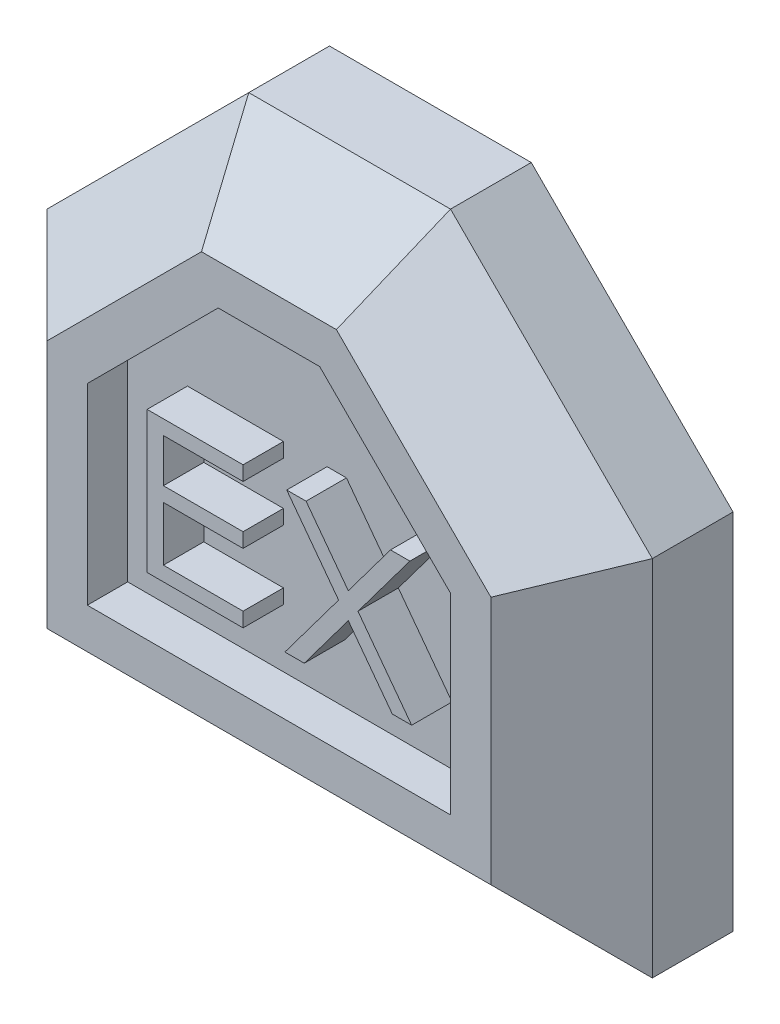
SolidWorks part; units mm, degrees
ref_plane "前视基准面" through (0, 0, 0) normal (0, 0, 1) x (1, 0, 0)
ref_plane "上视基准面" through (0, 0, 0) normal (0, 1, 0) x (1, 0, 0)
ref_plane "右视基准面" through (0, 0, 0) normal (1, 0, 0) x (0, 0, -1)
sketch "草图1" plane through (0, 0, 0) normal (0, 0, 1) x (1, 0, 0)
  line L0 (-7.5, 2) -> (-2.5, 7)
  line L1 (-7.5, -7) -> (7.5, -7)
  line L2 (-7.5, -7) -> (-7.5, 2)
  line L3 (-2.5, 7) -> (2.5, 7)
  line L4 (7.5, -7) -> (7.5, 2)
  line L5 (-7.5, -7) -> (7.5, 7) construction
  line L6 (-7.5, 7) -> (7.5, -7) construction
  line L7 (2.5, 7) -> (7.5, 2)
  point P0 (0, 0)
  dimension "D1" = 14
  dimension "D2" = 15
extrude "凸台-拉伸1" add sketch "草图1" along normal blind 4
chamfer "倒角1" distance 2 angle 45 6 edges at (-5, 4.5, 4) (0, 7, 4) (5, 4.5, 4) (7.5, -2.5, 4) (0, -7, 4) (-7.5, -2.5, 4)
sketch "草图2" plane through (0, 0, 4) normal (0, 0, 1) x (1, 0, 0)
  line L12 (5.8137, 15) -> (-5.8137, 15)
  line L13 (-5.8137, 15) -> (-15.5, 5.3137)
  line L14 (-15.5, 5.3137) -> (-15.5, -15)
  line L15 (-15.5, -15) -> (15.5, -15)
  line L16 (15.5, -15) -> (15.5, 5.3137)
  line L17 (15.5, 5.3137) -> (5.8137, 15)
  line L18 (5.8137, 15) -> (-5.8137, 15)
  line L19 (-5.8137, 15) -> (-15.5, 5.3137)
  line L20 (-15.5, 5.3137) -> (-15.5, -15)
  line L21 (-15.5, -15) -> (15.5, -15)
  line L22 (15.5, -15) -> (15.5, 5.3137)
  line L23 (15.5, 5.3137) -> (5.8137, 15)
  line L30 (-4.5, -4) -> (4.5, -4)
  line L31 (4.5, -4) -> (4.5, 0.7574)
  line L32 (4.5, 0.7574) -> (1.2574, 4)
  line L33 (1.2574, 4) -> (-1.2574, 4)
  line L34 (-1.2574, 4) -> (-4.5, 0.7574)
  line L35 (-4.5, 0.7574) -> (-4.5, -4)
  line L36 (-4.5, -4) -> (4.5, -4)
  line L37 (4.5, -4) -> (4.5, 0.7574)
  line L38 (4.5, 0.7574) -> (1.2574, 4)
  line L39 (1.2574, 4) -> (-1.2574, 4)
  line L40 (-1.2574, 4) -> (-4.5, 0.7574)
  line L41 (-4.5, 0.7574) -> (-4.5, -4)
  dimension "D1" = 10
  dimension "D2" = 1
extrude "切除-拉伸1" cut sketch "草图2" against normal blind 1 contours L40 L41 L36 L37 L38 L39
sketch "草图3" plane through (0, 0, 3) normal (0, 0, 1) x (1, 0, 0)
  text T0 "EX" font "Century Gothic" height 3.5
extrude "凸台-拉伸2" add sketch "草图3" along normal blind 1
